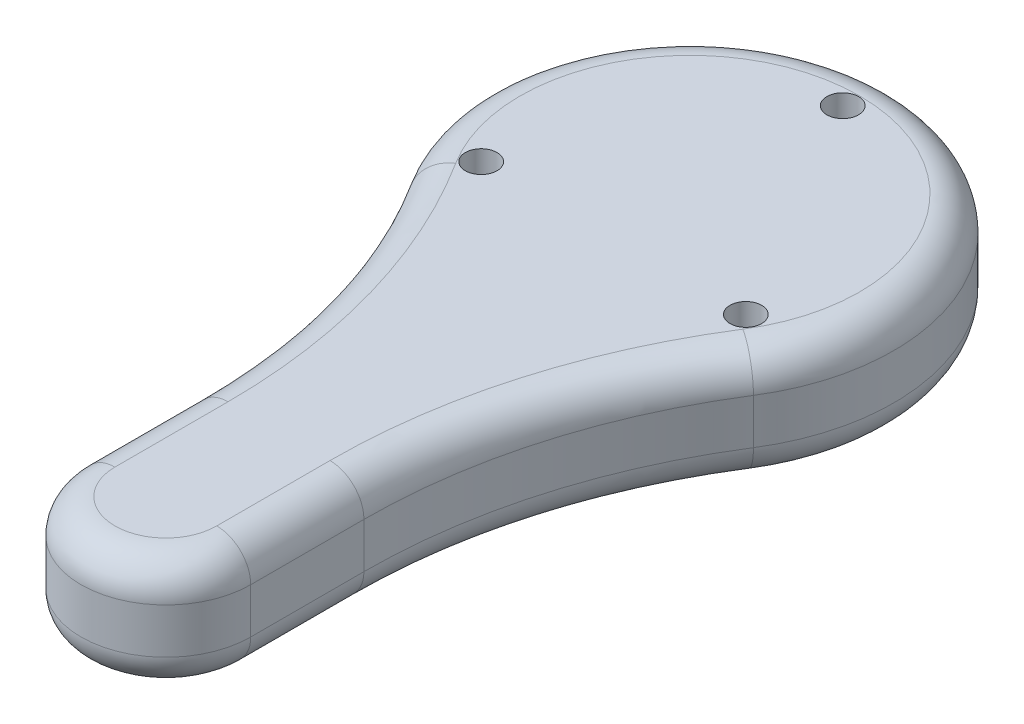
SolidWorks part; units mm, degrees
ref_plane "Front Plane" through (0, 0, 0) normal (0, 0, 1) x (1, 0, 0)
ref_plane "Top Plane" through (0, 0, 0) normal (0, 1, 0) x (1, 0, 0)
ref_plane "Right Plane" through (0, 0, 0) normal (1, 0, 0) x (0, 0, -1)
sketch "Sketch1" plane through (0, 0, 0) normal (0, 1, 0) x (1, 0, 0)
  line L0 (0, 0) -> (0, -46.3008) construction
  line L1 (7.5, -36.3008) -> (7.5, -46.3008)
  line L2 (-7.5, -36.3008) -> (-7.5, -46.3008)
  arc A0 (15.2206, -9.609) -> (-15.2206, -9.609) centre (0, 0) ccw
  arc A2 (-7.5, -46.3008) -> (7.5, -46.3008) centre (0, -46.3008) ccw
  arc A3 (15.2206, -9.609) -> (7.5, -36.3008) centre (57.5, -36.3008) ccw
  arc A4 (-7.5, -36.3008) -> (-15.2206, -9.609) centre (-57.5, -36.3008) ccw
  dimension "D1" = 36
  dimension "D2" = 50
  dimension "D3" = 10
  dimension "D4" = 15
extrude "Boss-Extrude1" add sketch "Sketch1" along normal blind 10
fillet "Fillet1" radius 3 12 edges at (0, 0, -18) (-9.4689, 0, 22.4079) (-7.5, 0, 41.3008) (0, 0, 53.8008) (7.5, 0, 41.3008) (9.4689, 0, 22.4079) (7.5, 10, 41.3008) (0, 10, 53.8008) (-7.5, 10, 41.3008) (-9.4689, 10, 22.4079) (0, 10, -18) (9.4689, 10, 22.4079)
sketch "Sketch2" plane through (0, 10, 0) normal (0, 1, 0) x (1, 0, 0)
  arc A0 (-11.6913, -7.775) -> (-11.6913, -5.725) centre (-11.6913, -6.75) ccw construction
  arc A1 (11.6913, -7.775) -> (11.6913, -5.725) centre (11.6913, -6.75) ccw construction
  arc A2 (0, 12.475) -> (0, 14.525) centre (0, 13.5) ccw construction
  arc A3 (-11.6913, -7.775) -> (-11.6913, -5.725) centre (-11.6913, -6.75) ccw construction
  arc A4 (11.6913, -7.775) -> (11.6913, -5.725) centre (11.6913, -6.75) ccw construction
  arc A5 (0, 12.475) -> (0, 14.525) centre (0, 13.5) ccw construction
  circle A6 centre (0, 13.5) radius 1.4
  circle A7 centre (-11.6913, -6.75) radius 1.4
  circle A8 centre (11.6913, -6.75) radius 1.4
  dimension "D1" = 2.8
extrude "Cut-Extrude1" cut sketch "Sketch2" against normal through all
sketch "Sketch3" plane through (0, 10, 0) normal (0, 1, 0) x (1, 0, 0)
  circle A0 centre (0, 0) radius 53.8008
